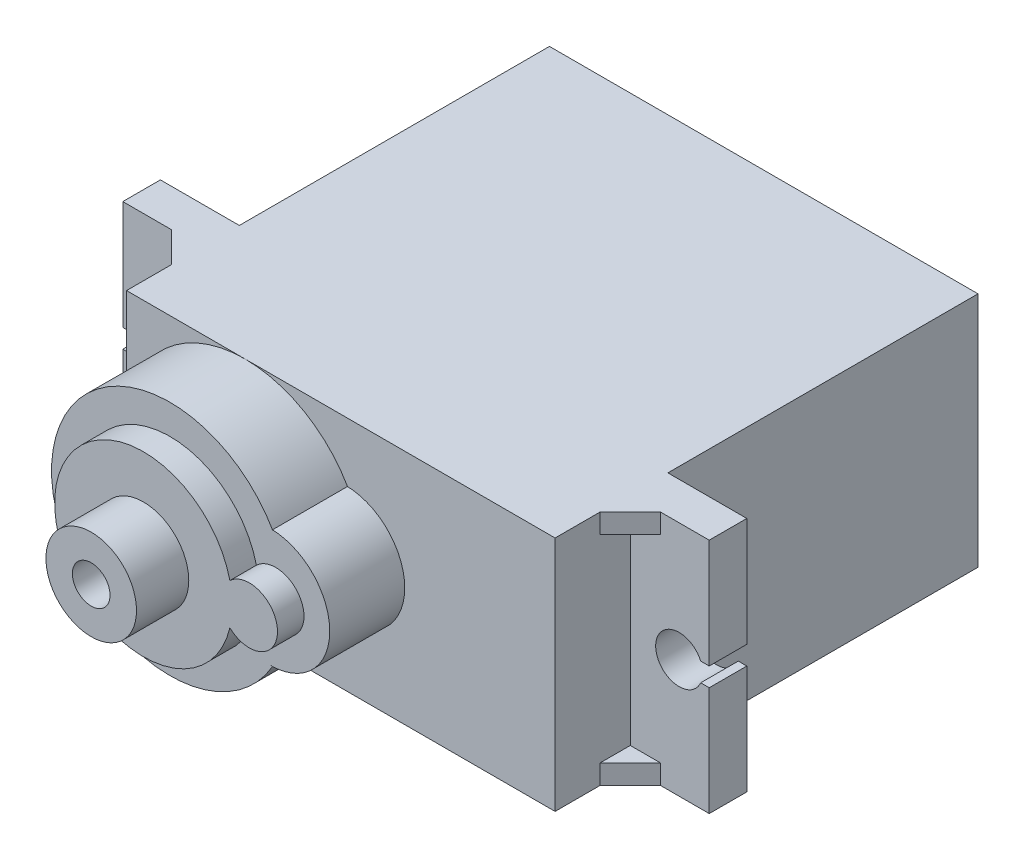
SolidWorks part; units mm, degrees
ref_plane "Plan de face" through (0, 0, 0) normal (0, 0, 1) x (1, 0, 0)
ref_plane "Plan de dessus" through (0, 0, 0) normal (0, 1, 0) x (1, 0, 0)
ref_plane "Plan de droite" through (0, 0, 0) normal (1, 0, 0) x (0, 0, -1)
sketch "Esquisse1" plane through (0, 0, 0) normal (0, 0, 1) x (1, 0, 0)
  line L1 (0, 0) -> (-22.8, 0)
  line L2 (0, 0) -> (0, 12.6)
  line L3 (0, 12.6) -> (-22.8, 12.6)
  line L4 (-22.8, 0) -> (-22.8, 12.6)
  dimension "D1" = 22.8
  dimension "D2" = 12.6
extrude "Boss.-Extru.1" add sketch "Esquisse1" along normal blind 22.5
ref_plane "Plan1" through (0, 0, 18.5) normal (0, 0, 1) x (1, 0, 0)
sketch "Esquisse2" plane through (0, 0, 18.5) normal (0, 0, 1) x (1, 0, 0)
  line L0 (0, 12.6) -> (-22.8, 12.6) construction
  line L1 (-27, 12.6) -> (4.2, 12.6)
  line L2 (-27, 12.6) -> (-27, 0)
  line L3 (-27, 0) -> (4.2, 0)
  line L4 (4.2, 12.6) -> (4.2, 0)
  line L5 (-22.8, 0) -> (0, 0) construction
  point P4 (-11.4, 12.6)
  point P5 (-11.4, 12.6)
  dimension "D1" = 31.2
extrude "Boss.-Extru.2" add sketch "Esquisse2" against normal blind 2
sketch "Esquisse3" plane through (0, 0, 18.5) normal (0, 0, 1) x (1, 0, 0)
  line L0 (-27, 6.3) -> (4.2, 6.3) construction
  line L1 (-27, 12.6) -> (-27, 0) construction
  line L2 (4.2, 0) -> (4.2, 12.6) construction
  line L3 (-11.4, 6.3) -> (-11.4, 17.6002) construction
  line L4 (3.7456, 6.8) -> (4.2, 6.8)
  line L5 (4.2, 6.8) -> (4.2, 5.8)
  line L6 (3.7456, 5.8) -> (4.2, 5.8)
  line L7 (-26.5456, 5.8) -> (-27, 5.8)
  line L8 (-27, 6.8) -> (-27, 5.8)
  line L9 (-26.5456, 6.8) -> (-27, 6.8)
  arc A0 (3.7456, 6.8) -> (3.7456, 5.8) centre (2.6, 6.3) ccw
  circle A1 centre (2.6, 6.3) radius 1.25 construction
  circle A2 centre (-25.4, 6.3) radius 1.25 construction
  arc A3 (-26.5456, 6.8) -> (-26.5456, 5.8) centre (-25.4, 6.3) cw
  dimension "D1" = 2.5
  dimension "D2" = 1
  dimension "D3" = 28
extrude "Enlèv. mat.-Extru.1" cut sketch "Esquisse3" against normal through all
sketch "Esquisse4" plane through (0, 0, 22.5) normal (0, 0, 1) x (1, 0, 0)
  line L0 (0, 12.6) -> (-22.8, 12.6) construction
  line L1 (-22.8, 12.6) -> (-22.8, 0) construction
  line L2 (-22.8, 0) -> (0, 0) construction
  line L3 (-11.15, 9.45) -> (-11.044, 9.45)
  line L4 (-11.15, 3.15) -> (-11.044, 3.15)
  line L5 (-25.4, 6.3) -> (-11.15, 6.3) construction
  circle A0 centre (-16.5, 6.3) radius 6.3 construction
  circle A1 centre (-11.15, 6.3) radius 3.15 construction
  arc A2 (-11.15, 9.45) -> (-11.15, 3.15) centre (-11.15, 6.3) cw
  arc A3 (-11.044, 9.45) -> (-11.044, 3.15) centre (-16.5, 6.3) ccw
  point P16 (-14.3, 6.3)
  point P17 (-22.8, 6.3)
  point P19 (-8, 6.3)
  dimension "D1" = 6.3
  dimension "D2" = 14.8
extrude "Boss.-Extru.3" add sketch "Esquisse4" along normal blind 3.99
sketch "Sketch1" plane through (0, 0, 26.49) normal (0, 0, 1) x (1, 0, 0)
  circle A0 centre (-16.5, 6.3) radius 4.725
  circle A1 centre (-10.87, 6.3) radius 1.5
  arc A3 (-11.15, 3.15) -> (-11.15, 9.45) centre (-11.15, 6.3) ccw construction
  point P5 (-8, 6.3)
  dimension "D1" = 9.45
  dimension "D2" = 3
  dimension "D3" = 2.87
extrude "Boss-Extrude6" add sketch "Sketch1" along normal blind 1.41 and the other way blind 4 contours A0 A1 | A1 A0 | A0 A1
sketch "Sketch3" plane through (0, 0, 27.9) normal (0, 0, 1) x (1, 0, 0)
  circle A0 centre (-16.5, 6.3) radius 2.41
  dimension "D1" = 4.82
extrude "Boss-Extrude7" add sketch "Sketch3" along normal blind 2.78
sketch "Sketch4" plane through (0, 0, 30.68) normal (0, 0, 1) x (1, 0, 0)
  circle A0 centre (-16.5, 6.3) radius 1
  dimension "D1" = 2
extrude "Cut-Extrude1" cut sketch "Sketch4" against normal blind 9.78
sketch "Sketch8" plane through (0, 0, 18.5) normal (0, 0, 1) x (1, 0, 0)
  line L1 (0, 0) -> (1.6, 0)
  line L2 (0, 0) -> (0, 1.04)
  line L3 (0, 1.04) -> (1.6, 1.04)
  line L4 (1.6, 0) -> (1.6, 1.04)
  dimension "D1" = 1.6
  dimension "D2" = 1.04
extrude "Boss-Extrude9" add sketch "Sketch8" along normal blind 1.6 contours L4 L3 L2 L1
sketch "Sketch9" plane through (0, 1.04, 0) normal (0, 1, 0) x (1, 0, 0)
  line L0 (1.6, -18.5) -> (0, -20.1)
  line L1 (0, -20.1) -> (1.6, -20.1)
  line L2 (1.6, -20.1) -> (1.6, -18.5)
extrude "Cut-Extrude3" cut sketch "Sketch9" against normal through all
ref_plane "Plane1" through (-11.4, 0, 0) normal (1, 0, 0) x (0, 0, -1)
ref_plane "Plane2" through (0, 6.3, 0) normal (0, -1, 0) x (-1, 0, 0)
mirror "Mirror1" about plane through (0, 6.3, 0) normal (0, -1, 0) of "Boss.-Extru.1", "Boss-Extrude9", "Cut-Extrude3"
mirror "Mirror3" about plane through (-11.4, 0, 0) normal (1, 0, 0) of "Mirror1", "Boss-Extrude9", "Boss.-Extru.1", "Cut-Extrude3"
